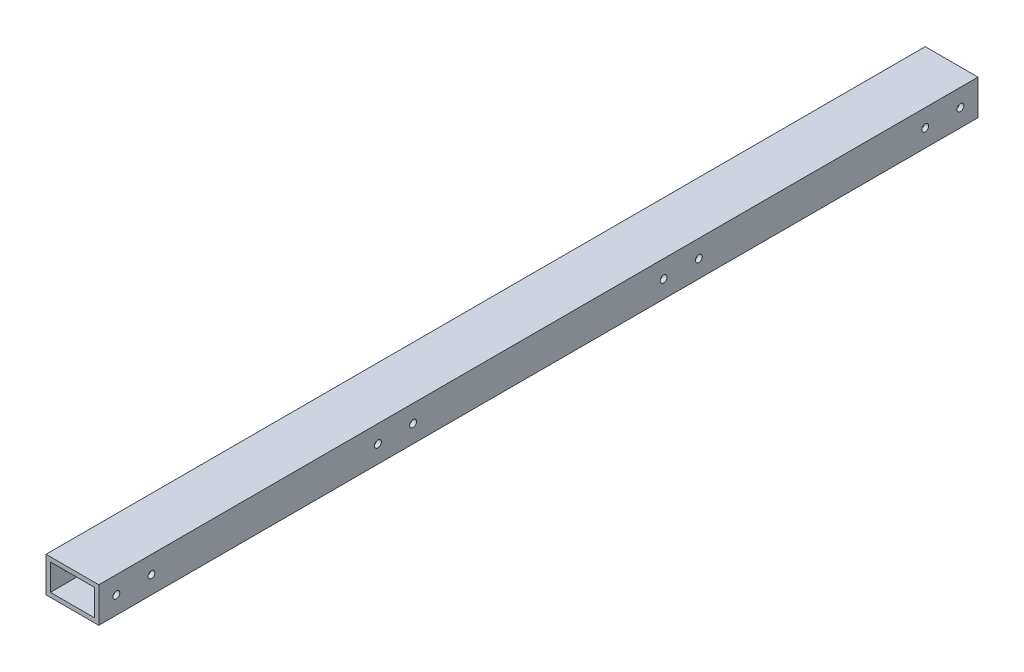
SolidWorks part; units mm, degrees
ref_plane "Front Plane" through (0, 0, 0) normal (0, 0, 1) x (1, 0, 0)
ref_plane "Top Plane" through (0, 0, 0) normal (0, 1, 0) x (1, 0, 0)
ref_plane "Right Plane" through (0, 0, 0) normal (1, 0, 0) x (0, 0, -1)
sketch "Sketch1" plane through (0, 0, 0) normal (0, 0, 1) x (1, 0, 0)
  line L0 (-15.875, 9.525) -> (15.875, 9.525)
  line L2 (-19.05, 12.7) -> (19.05, 12.7)
  line L3 (-19.05, 12.7) -> (-19.05, -12.7)
  line L4 (-19.05, -12.7) -> (19.05, -12.7)
  line L5 (19.05, 12.7) -> (19.05, -12.7)
  line L10 (15.875, 9.525) -> (15.875, -9.525)
  line L11 (-15.875, -9.525) -> (15.875, -9.525)
  line L12 (-15.875, 9.525) -> (-15.875, -9.525)
  point P12 (0, 12.7)
  point P14 (19.05, 0)
  dimension "Wall Thickness" = 3.175
  dimension "Outside Width" = 38.1
  dimension "Outside Height" = 25.4
  dimension "Inside Height" = 19.05
  dimension "Inside Width" = 31.75
sketch "Sketch2" plane through (0, 0, 0) normal (1, 0, 0) x (0, 0, -1)
  line L0 (330.2, 0) -> (-330.2, 0)
  point P4 (0, 0)
  point P7 (-330.2, 0)
  point P10 (330.2, 0)
  dimension "Length" = 660.4
sketch "Sketch3" plane through (0, 0, 0) normal (0, 0, 1) x (1, 0, 0)
  line L21 (19.05, 12.7) -> (-19.05, 12.7)
  line L22 (19.05, -12.7) -> (19.05, 12.7)
  line L23 (-19.05, -12.7) -> (19.05, -12.7)
  line L24 (-19.05, 12.7) -> (-19.05, -12.7)
  line L25 (19.05, 12.7) -> (-19.05, 12.7)
  line L26 (19.05, -12.7) -> (19.05, 12.7)
  line L27 (-19.05, -12.7) -> (19.05, -12.7)
  line L28 (-19.05, 12.7) -> (-19.05, -12.7)
  line L29 (15.875, 9.525) -> (-15.875, 9.525)
  line L30 (15.875, -9.525) -> (15.875, 9.525)
  line L31 (-15.875, -9.525) -> (15.875, -9.525)
  line L32 (-15.875, 9.525) -> (-15.875, -9.525)
  line L33 (15.875, 9.525) -> (-15.875, 9.525)
  line L34 (15.875, -9.525) -> (15.875, 9.525)
  line L35 (-15.875, -9.525) -> (15.875, -9.525)
  line L36 (-15.875, 9.525) -> (-15.875, -9.525)
  dimension "D1" = 0
  dimension "D2" = 0
extrude "Boss-Extrude1" add sketch "Sketch3" along normal up to vertex (330.2 mm away) and the other way up to vertex (330.2 mm away) up to point (0, 0, 330.2) other way up to point (0, 0, -330.2)
sketch "Drawing Reference" plane through (0, 0, 0) normal (1, 0, 0) x (0, 0, -1)
  line L0 (-330.2, 0) -> (330.2, 0) construction
  line L1 (0, -12.7) -> (0, 12.7) construction
  line L2 (-330.2, -12.7) -> (330.2, -12.7) construction
  line L5 (-330.2, 12.7) -> (330.2, 12.7) construction
  point P7 (-302.768, 0)
  point P8 (302.768, 0)
  dimension "D1" = 27.432
ref_plane "Plane1" through (0, 0, -304.8) normal (0, 0, -1) x (-1, 0, 0)
other "SurfaceCut1"
sketch "Sketch13" plane through (19.05, 0, 0) normal (1, 0, 0) x (0, 0, -1)
  line L0 (-103.1875, 0) -> (-128.5875, 0) construction
  line L1 (77.7875, 0) -> (103.1875, 0) construction
  line L2 (-330.2, 0) -> (-317.5, 0) construction
  line L3 (-330.2, -12.7) -> (-330.2, 12.7) construction
  line L4 (-317.5, 0) -> (-292.1, 0) construction
  line L5 (304.8, 0) -> (292.1, 0) construction
  line L7 (304.8, 12.7) -> (304.8, -12.7) construction
  line L8 (292.1, 0) -> (266.7, 0) construction
  point P19 (0, 0)
hole_wizard "#10 Clearance Hole1" positions "Sketch14" profile "Sketch15" hole size "#10" standard "ANSI Inch" end condition through all
sketch "Sketch14" plane through (19.05, 0, 0) normal (1, 0, 0) x (0, 0, -1)
  point P0 (-128.5875, 0)
  point P3 (-103.1875, 0)
  point P7 (77.7875, 0)
  point P10 (103.1875, 0)
  point P13 (-317.5, 0)
  point P16 (-292.1, 0)
  point P19 (266.7, 0)
  point P22 (292.1, 0)
sketch "Sketch15" plane through (19.05, 0, 128.5875) normal (0, 1, 0) x (0, 0, -1)
  line L0 (0, 0) -> (0, 38.1)
  line L1 (0, 38.1) -> (2.4892, 38.1)
  line L2 (2.4892, 38.1) -> (2.4892, 0)
  line L5 (2.4892, 0) -> (0, 0)
  line L11 (0, -6.35) -> (0, 107.95) construction
  dimension "Thru Hole Dia." = 4.9784
  dimension "Thru Hole Depth" = 38.1
equation "\"D1@Drawing Reference\"=\"Outside Width@Sketch1\" * 0.72"
